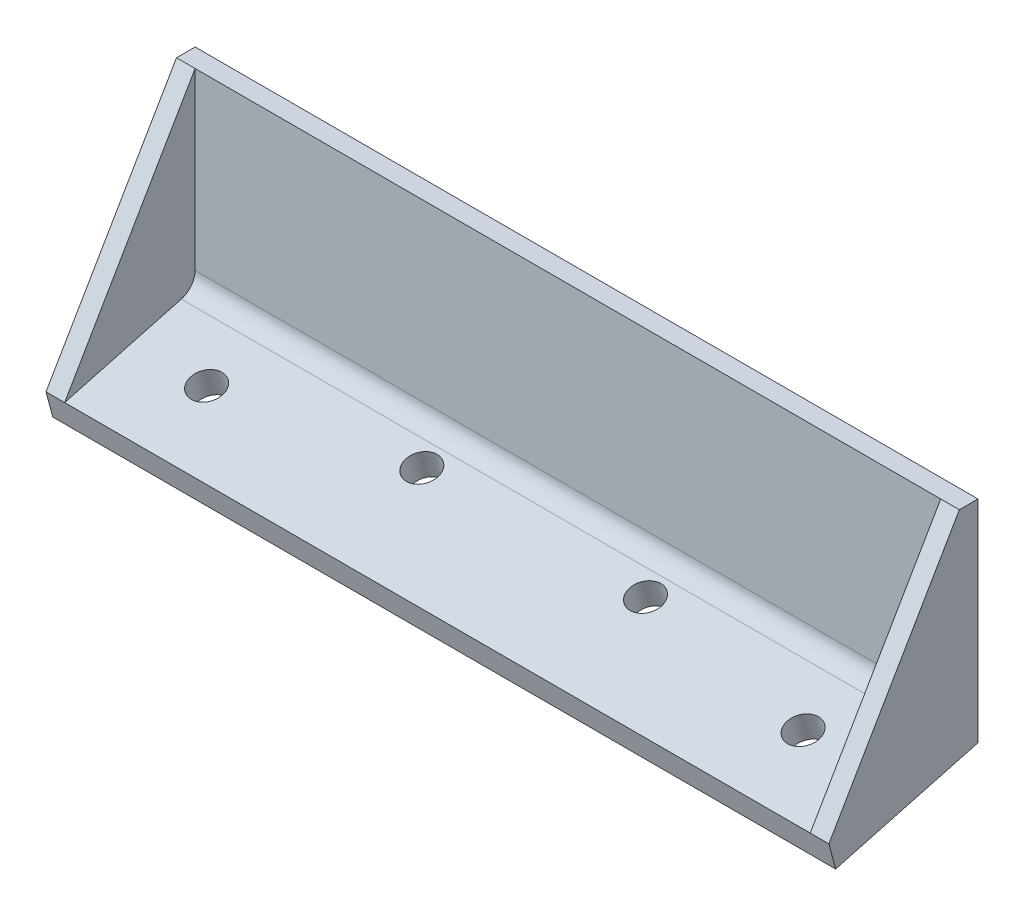
SolidWorks part; units mm, degrees
material "1060 合金"
ref_plane "前视基准面" through (0, 0, 0) normal (0, 0, 1) x (1, 0, 0)
ref_plane "上视基准面" through (0, 0, 0) normal (0, 1, 0) x (1, 0, 0)
ref_plane "右视基准面" through (0, 0, 0) normal (1, 0, 0) x (0, 0, -1)
sketch "草图1" plane through (0, 0, 0) normal (0, 1, 0) x (1, 0, 0)
  line L0 (0, 0) -> (170, 0) construction
  line L1 (170, 31.93) -> (170, -31.93)
  line L2 (15.8391, 73.3084) -> (162.1119, 41.7045)
  line L3 (15.8391, -73.3084) -> (162.1119, -41.7045)
  arc A0 (15.8391, 73.3084) -> (15.8391, -73.3084) centre (0, 0) ccw
  arc A1 (162.1119, -41.7045) -> (170, -31.93) centre (160, -31.93) ccw
  arc A2 (170, 31.93) -> (162.1119, 41.7045) centre (160, 31.93) ccw
  point P6 (170, 0)
  dimension "D1" = 150
  dimension "D4" = 20
  dimension "D5" = 20
  dimension "D2" = 170
  dimension "D3" = 63.86
extrude "凸台-拉伸1" add sketch "草图1" along normal blind 30
sketch "草图2" plane through (0, 30, 0) normal (0, 1, 0) x (1, 0, 0)
  circle A0 centre (0, 0) radius 44.45
  dimension "D1" = 88.9
extrude "切除-拉伸1" cut sketch "草图2" against normal blind 4
sketch "草图3" plane through (0, 26, 0) normal (0, 1, 0) x (1, 0, 0)
  line L0 (0, 0) -> (0, 90.3276) construction
  circle A0 centre (0, 0) radius 25.5
  circle A1 centre (0, 41) radius 2.25
  circle A2 centre (28.9914, 28.9914) radius 2.25
  circle A3 centre (41, 0) radius 2.25
  circle A4 centre (28.9914, -28.9914) radius 2.25
  circle A5 centre (0, -41) radius 2.25
  circle A6 centre (-28.9914, -28.9914) radius 2.25
  circle A7 centre (-41, 0) radius 2.25
  circle A8 centre (-28.9914, 28.9914) radius 2.25
  dimension "D1" = 51
  dimension "D3" = 4.5
  dimension "D2" = 41
  dimension "D4" = 8
extrude "切除-拉伸2" cut sketch "草图3" against normal through all contours A2 | A3 | A4 | A5 | A6 | A7 | A8 | A1 | A0
sketch "草图4" plane through (0, 30, 0) normal (0, 1, 0) x (1, 0, 0)
  line L0 (0, 0) -> (134, 0) construction
  line L1 (124, 18.5) -> (134, 18.5)
  line L2 (124, -18.5) -> (134, -18.5)
  arc A0 (134, -18.5) -> (134, 18.5) centre (134, 0) ccw
  arc A1 (124, 18.5) -> (124, -18.5) centre (124, 0) ccw
  dimension "D2" = 37
  dimension "D3" = 37
  dimension "D1" = 134
  dimension "D4" = 10
extrude "切除-拉伸3" cut sketch "草图4" against normal through all
sketch "草图5" plane through (0, 30, 0) normal (0, 1, 0) x (1, 0, 0)
  arc A0 (134, -18.5) -> (134, 18.5) centre (134, 0) ccw construction
  arc A1 (124, 18.5) -> (124, -18.5) centre (124, 0) ccw construction
  arc A2 (134, -18.5) -> (134, 18.5) centre (134, 0) ccw construction
  arc A3 (124, 18.5) -> (124, -18.5) centre (124, 0) ccw construction
  circle A4 centre (116.75, 25.5) radius 1.65
  circle A5 centre (141.25, 25.5) radius 1.65
  circle A6 centre (141.25, -25.5) radius 1.65
  circle A7 centre (116.75, -25.5) radius 1.65
  dimension "D1" = 3.3
  dimension "D2" = 3.3
  dimension "D3" = 3.3
  dimension "D4" = 3.3
  dimension "D7" = 25.5
  dimension "D5" = 7.25
  dimension "D6" = 25.5
  dimension "D8" = 7.25
  dimension "D9" = 7.25
extrude "切除-拉伸4" cut sketch "草图5" against normal through all
sketch "草图6" plane through (0, 30, 0) normal (0, 1, 0) x (1, 0, 0)
  line L0 (158, 42.5929) -> (158, -42.5929) construction
  line L2 (-52, 54.0463) -> (-52, -54.0463) construction
  line L6 (162.1119, 41.7045) -> (15.8391, 73.3084) construction
  line L7 (15.8391, -73.3084) -> (162.1119, -41.7045) construction
  line L8 (-52, 95) -> (-52, -95)
  line L9 (158, 95) -> (158, -95)
  line L10 (-52, 95) -> (158, 95)
  line L11 (-52, -95) -> (158, -95)
  line L15 (162.1119, 41.7045) -> (15.8391, 73.3084)
  line L16 (15.8391, -73.3084) -> (162.1119, -41.7045)
  line L17 (170, -31.93) -> (170, 31.93)
  line L18 (162.1119, 41.7045) -> (15.8391, 73.3084)
  line L19 (15.8391, -73.3084) -> (162.1119, -41.7045)
  line L20 (170, -31.93) -> (170, 31.93)
  arc A0 (15.8391, 73.3084) -> (15.8391, -73.3084) centre (0, 0) ccw construction
  arc A6 (170, 31.93) -> (162.1119, 41.7045) centre (160, 31.93) ccw
  arc A7 (15.8391, 73.3084) -> (15.8391, -73.3084) centre (0, 0) ccw
  arc A8 (162.1119, -41.7045) -> (170, -31.93) centre (160, -31.93) ccw
  arc A9 (170, 31.93) -> (162.1119, 41.7045) centre (160, 31.93) ccw
  arc A10 (15.8391, 73.3084) -> (15.8391, -73.3084) centre (0, 0) ccw
  arc A11 (162.1119, -41.7045) -> (170, -31.93) centre (160, -31.93) ccw
  point P8 (-52, 0)
  point P13 (158, 0)
  line M26 (162.1119, 41.7045) -> (15.8391, 73.3084)
  arc M27 (15.8391, 73.3084) -> (15.8391, -73.3084) centre (0, 0) ccw
  line M28 (15.8391, -73.3084) -> (162.1119, -41.7045)
  dimension "D3" = 190
  dimension "D1" = 210
  dimension "D2" = 52
  dimension "D4" = 190
  dimension "D5" = 0
extrude "凸台-拉伸2" add sketch "草图6" against normal blind 30 contours L10 L8 L9 M27 M26 | L8 L11 L9 M28 M27
sketch "草图7" plane through (0, 30, 0) normal (0, 1, 0) x (1, 0, 0)
  line L0 (-52, 54.0463) -> (-52, -54.0463)
  line L1 (158, 42.5929) -> (158, -42.5929)
  line L9 (162.1119, 41.7045) -> (158, 42.5929)
  line L10 (158, 42.5929) -> (158, 95)
  line L11 (158, 95) -> (-52, 95)
  line L12 (-52, 95) -> (-52, 54.0463)
  line L13 (-52, -54.0463) -> (-52, -95)
  line L14 (-52, -95) -> (158, -95)
  line L15 (158, -95) -> (158, -42.5929)
  line L16 (158, -42.5929) -> (162.1119, -41.7045)
  line L17 (170, -31.93) -> (170, 31.93)
  line L18 (162.1119, 41.7045) -> (158, 42.5929)
  line L21 (-52, 95) -> (-52, 54.0463)
  line L25 (158, -42.5929) -> (162.1119, -41.7045)
  line L26 (170, -31.93) -> (170, 31.93)
  arc A3 (170, 31.93) -> (162.1119, 41.7045) centre (160, 31.93) ccw
  arc A4 (-52, 54.0463) -> (-52, -54.0463) centre (0, 0) ccw
  arc A5 (162.1119, -41.7045) -> (170, -31.93) centre (160, -31.93) ccw
  arc A6 (170, 31.93) -> (162.1119, 41.7045) centre (160, 31.93) ccw
  arc A7 (-52, 54.0463) -> (-52, -54.0463) centre (0, 0) ccw
  arc A8 (162.1119, -41.7045) -> (170, -31.93) centre (160, -31.93) ccw
  arc M22 (170, 31.93) -> (162.1119, 41.7045) centre (160, 31.93) ccw
  line M23 (162.1119, 41.7045) -> (158, 42.5929)
  arc M27 (-52, 54.0463) -> (-52, -54.0463) centre (0, 0) ccw
  line M31 (158, -42.5929) -> (162.1119, -41.7045)
  arc M32 (162.1119, -41.7045) -> (170, -31.93) centre (160, -31.93) ccw
  line M33 (170, -31.93) -> (170, 31.93)
  dimension "D1" = 0
extrude "切除-拉伸5" cut sketch "草图7" against normal through all contours L0 M27 | L1 M23 M31 M32 M33 M22
sketch "草图9" plane through (-52, 0, 0) normal (-1, 0, 0) x (0, 0, 1)
  line L0 (-95, 20) -> (-60, 10.6218)
  line L1 (-95, 30) -> (95, 30) construction
  line L3 (-60, 10.6218) -> (-60, 30)
  line L5 (-95, 0) -> (-95, 30) construction
  line L7 (-95, 20) -> (-95, 30)
  line L8 (-95, 30) -> (-60, 30)
  dimension "D1" = 15
  dimension "D3" = 19.3782
  dimension "D4" = 35
  dimension "D5" = 10
extrude "切除-拉伸7" cut sketch "草图9" against normal through all contours L8 L3 L0 L7
sketch "草图8" plane through (-52, 0, 0) normal (-1, 0, 0) x (0, 0, 1)
  line L0 (0, 0) -> (52, 0)
  line L1 (-95, 0) -> (95, 0) construction
  line L2 (52, 0) -> (52, 17.3)
  line L3 (52, 17.3) -> (-52, 17.3)
  line L4 (-52, 17.3) -> (-52, 0)
  line L5 (-52, 0) -> (0, 0)
  line L6 (-60, 30) -> (95, 30) construction
  dimension "D1" = 52
  dimension "D2" = 52
  dimension "D3" = 12.7
sketch "草图10" plane through (-52, 0, 0) normal (-1, 0, 0) x (0, 0, 1)
  line L0 (-95, 12.7531) -> (-47.4049, 0) construction
  line L1 (-95, 0) -> (-95, 20) construction
  line L2 (-95, 0) -> (95, 0) construction
  line L3 (-95, 20) -> (-60, 10.6218) construction
  line L6 (-95, 12.7531) -> (-52, 1.2313)
  line L7 (-52, 1.2313) -> (-52, 0)
  line L8 (-95, 12.7531) -> (-95, 0)
  line L9 (-95, 0) -> (-52, 0)
  line L10 (-52, 17.3) -> (-52, 0) construction
  dimension "D1" = 7
extrude "切除-拉伸8" cut sketch "草图10" against normal through all
extrude "切除-拉伸9" cut sketch "草图8" against normal through all
fillet "圆角1" radius 5 1 edges at (53, 10.6218, -60)
sketch "草图11" plane through (-52, 0, 0) normal (-1, 0, 0) x (0, 0, 1)
  line L0 (-95, 12.7531) -> (-93.1883, 19.5145)
  line L1 (-95, 20) -> (-66.2941, 12.3083) construction
  line L2 (-93.1883, 19.5145) -> (-95, 20)
  line L3 (-95, 20) -> (-95, 12.7531)
extrude "切除-拉伸10" cut sketch "草图11" against normal through all
sketch "草图12" plane through (-52, 0, 0) normal (-1, 0, 0) x (0, 0, 1)
  line L0 (-93.1883, 19.5145) -> (-60, 30)
  line L10 (-93.1883, 19.5145) -> (-95, 12.7531)
  line L11 (-95, 12.7531) -> (-52, 1.2313)
  line L12 (-52, 1.2313) -> (-52, 17.3)
  line L13 (-52, 17.3) -> (52, 17.3)
  line L14 (52, 17.3) -> (52, 0)
  line L15 (52, 0) -> (95, 0)
  line L16 (95, 0) -> (95, 30)
  line L17 (95, 30) -> (-60, 30)
  line L18 (-60, 30) -> (-60, 17.1379)
  line L19 (-66.2941, 12.3083) -> (-93.1883, 19.5145)
  line L28 (-60, 30) -> (-60, 17.1379)
  line L29 (-66.2941, 12.3083) -> (-93.1883, 19.5145)
  arc A1 (-66.2941, 12.3083) -> (-60, 17.1379) centre (-65, 17.1379) ccw
  arc A2 (-66.2941, 12.3083) -> (-60, 17.1379) centre (-65, 17.1379) ccw
  dimension "D1" = 0
extrude "凸台-拉伸3" add sketch "草图12" against normal blind 5
sketch "草图13" plane through (158, 0, 0) normal (1, 0, 0) x (0, 0, -1)
  line L3 (66.2941, 12.3083) -> (93.1883, 19.5145)
  line L4 (93.1883, 19.5145) -> (60, 30)
  line L5 (60, 30) -> (60, 17.1379)
  line L6 (66.2941, 12.3083) -> (93.1883, 19.5145)
  line L7 (93.1883, 19.5145) -> (60, 30)
  line L8 (60, 30) -> (60, 17.1379)
  arc A1 (60, 17.1379) -> (66.2941, 12.3083) centre (65, 17.1379) ccw
  arc A2 (60, 17.1379) -> (66.2941, 12.3083) centre (65, 17.1379) ccw
  dimension "D1" = 0
extrude "凸台-拉伸4" add sketch "草图13" against normal blind 5
sketch "草图14" plane through (0, -5.0897, -1.3638) normal (0, 0.9659, 0.2588) x (1, 0, 0)
  line L0 (153, 67.2208) -> (153, 95.0637) construction
  line L3 (153, 95.0637) -> (-47, 95.0637) construction
  circle A0 centre (-27, 82.0637) radius 4.25
  circle A1 centre (23, 82.0637) radius 4.25
  circle A2 centre (83, 82.0637) radius 4.25
  circle A3 centre (133, 82.0637) radius 4.25
  dimension "D1" = 8.5
  dimension "D2" = 160
  dimension "D3" = 20
  dimension "D4" = 50
  dimension "D5" = 50
  dimension "D6" = 13
extrude "切除-拉伸11" cut sketch "草图14" against normal through all
sketch "草图16" plane through (-52, 0, 0) normal (-1, 0, 0) x (0, 0, 1)
  line L0 (-60, 30) -> (95, 30) construction
  line L1 (95, 0) -> (52, 0)
  line L2 (95, 0) -> (95, 30)
  line L3 (95, 30) -> (52, 30)
  line L4 (52, 0) -> (52, 30)
extrude "切除-拉伸12" cut sketch "草图16" against normal through all
ref_plane "基准面1" through (0, -11.8512, -3.1755) normal (0, -0.9659, -0.2588) x (-1, 0, 0)
sketch "草图18" plane through (0, 30, 0) normal (0, 1, 0) x (1, 0, 0)
  line L1 (-52, -52) -> (158, -52)
  line L2 (-52, -52) -> (-52, -57)
  line L3 (-52, -57) -> (158, -57)
  line L4 (158, -52) -> (158, -57)
  dimension "D1" = 5
extrude "凸台-拉伸7" add sketch "草图18" against normal up to surface (56.6355 mm away) up to plane "基准面1"
sketch "草图19" plane through (-52, 0, 0) normal (-1, 0, 0) x (0, 0, 1)
  line L0 (57, -27.9752) -> (90.1883, -36.868)
  line L1 (90.1883, -36.868) -> (92, -30.1065)
  line L2 (92, -30.1065) -> (57, -20.7283)
  line L3 (57, -27.9752) -> (57, 30) construction
  line L4 (57, -20.7283) -> (57, -27.9752)
  line L5 (52, -26.6355) -> (57, -27.9752) construction
  dimension "D1" = 7
  dimension "D2" = 40
extrude "凸台-拉伸8" add sketch "草图19" against normal up to surface (210 mm away) up to face at (158, 8.1654, -14.9098)
sketch "草图20" plane through (-52, 0, 0) normal (-1, 0, 0) x (0, 0, 1)
  line L0 (92, -30.1065) -> (57, -20.7283) construction
  line L1 (57, -20.7283) -> (57, 30) construction
  line L2 (92, -30.1065) -> (57, -20.7283)
  line L3 (57, -20.7283) -> (57, 30)
  line L4 (57, 30) -> (92, -30.1065)
extrude "凸台-拉伸9" add sketch "草图20" against normal blind 5
sketch "草图21" plane through (158, 0, 0) normal (1, 0, 0) x (0, 0, -1)
  line L3 (-57, 30) -> (-92, -30.1065)
  line L4 (-92, -30.1065) -> (-57, -20.7283)
  line L5 (-57, -20.7283) -> (-57, 30)
  line L6 (-57, 30) -> (-92, -30.1065)
  line L7 (-92, -30.1065) -> (-57, -20.7283)
  line L8 (-57, -20.7283) -> (-57, 30)
  dimension "D1" = 0
extrude "凸台-拉伸10" add sketch "草图21" against normal blind 5
sketch "草图22" plane through (0, -5.0897, -1.3638) normal (0, 0.9659, 0.2588) x (1, 0, 0)
  line L0 (-47, -96.6573) -> (-47, -47.2932) construction
  line L2 (153, -96.6573) -> (153, -60.4226) construction
  circle A0 centre (-27, -77.9363) radius 4.25
  circle A1 centre (23, -69.9363) radius 4.25
  circle A2 centre (83, -69.9363) radius 4.25
  circle A3 centre (133, -77.9363) radius 4.25
  circle A4 centre (133, 82.0637) radius 4.25 construction
  circle A5 centre (-27, 82.0637) radius 4.25 construction
  circle A6 centre (23, 82.0637) radius 4.25 construction
  circle A7 centre (83, 82.0637) radius 4.25 construction
  dimension "D1" = 8.5
  dimension "D7" = 152
  dimension "D6" = 152
  dimension "D8" = 50
  dimension "D4" = 160
  dimension "D5" = 160
  dimension "D2" = 20
  dimension "D3" = 20
  dimension "D9" = 50
extrude "切除-拉伸13" cut sketch "草图22" against normal through all
fillet "圆角2" radius 5 1 edges at (53, -20.7283, 57)
sketch "草图23" plane through (-52, 0, 0) normal (-1, 0, 0) x (0, 0, 1)
  line L0 (52, -26.6355) -> (52, 17.3) construction
  line L1 (52, 56.9656) -> (-106.5122, 56.9656)
  line L2 (52, 56.9656) -> (52, -46.3521)
  line L3 (52, -46.3521) -> (-106.5122, -46.3521)
  line L4 (-106.5122, 56.9656) -> (-106.5122, -46.3521)
  point P6 (52, 56.9656)
  point P7 (52, -46.3521)
extrude "切除-拉伸14" cut sketch "草图23" against normal through all
